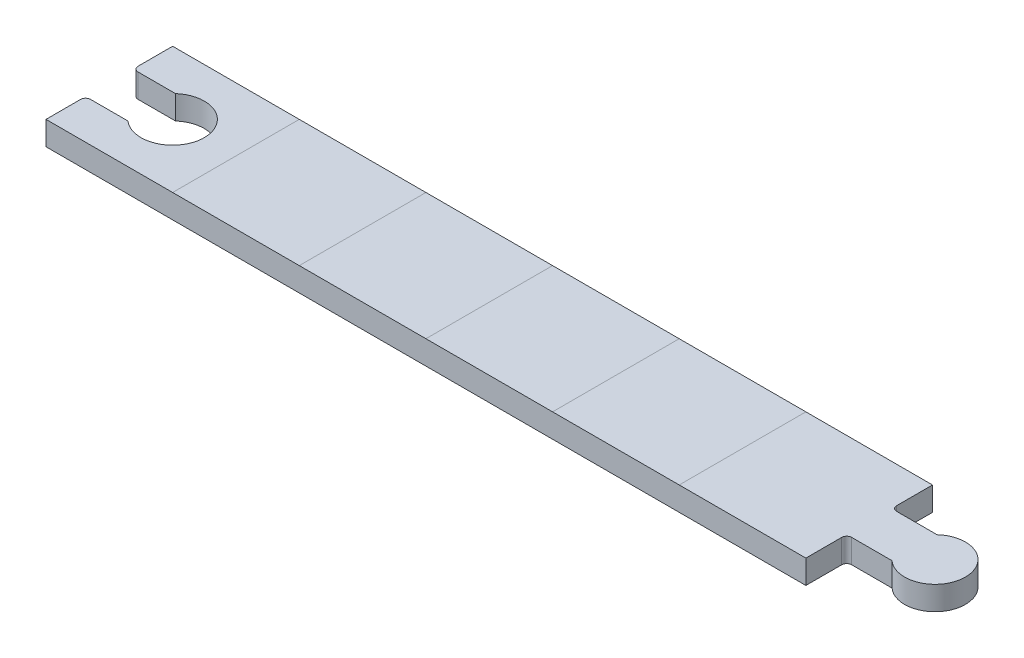
SolidWorks part; units mm, degrees
ref_plane "Front Plane" through (0, 0, 0) normal (0, 0, 1) x (1, 0, 0)
ref_plane "Top Plane" through (0, 0, 0) normal (0, 1, 0) x (1, 0, 0)
ref_plane "Right Plane" through (0, 0, 0) normal (1, 0, 0) x (0, 0, -1)
sketch "Sketch1" plane through (0, 0, 0) normal (0, 1, 0) x (1, 0, 0)
  line L0 (-76.2, 0) -> (95.5, 0) construction
  line L1 (-76.2, -12.7) -> (76.2, -12.7)
  line L2 (-76.2, -12.7) -> (-76.2, -4.7625)
  line L3 (-76.2, 12.7) -> (76.2, 12.7)
  line L4 (76.2, -12.7) -> (76.2, -4.5125)
  line L5 (-76.2, -12.7) -> (76.2, 12.7) construction
  line L6 (-76.2, 12.7) -> (76.2, -12.7) construction
  line L7 (76.2, 4.5125) -> (85.2954, 4.5125)
  line L8 (76.2, -4.5125) -> (85.2954, -4.5125)
  line L9 (76.2, 4.5125) -> (76.2, 12.7)
  line L10 (-67.7001, 4.7625) -> (-76.2, 4.7625)
  line L11 (-76.2, -4.7625) -> (-67.7001, -4.7625)
  line L12 (-76.2, 4.7625) -> (-76.2, 12.7)
  arc A0 (-67.7001, -4.7625) -> (-67.7001, 4.7625) centre (-63.5, 0) ccw
  arc A1 (85.2954, -4.5125) -> (85.2954, 4.5125) centre (89.4, 0) ccw
  point P0 (0, 0)
  dimension "D5" = 12.7
  dimension "D6" = 12.2
  dimension "D1" = 152.4
  dimension "D2" = 25.4
  dimension "D3" = 12.7
  dimension "D4" = 13.2
  dimension "D7" = 9.025
  dimension "D8" = 4.5125
  dimension "D9" = 9.525
  dimension "D10" = 4.7625
extrude "Boss-Extrude1" add sketch "Sketch1" along normal blind 4.7625
fillet "Fillet1" radius 1 4 edges at (-76.2, 2.3813, 4.7625) (-76.2, 2.3813, -4.7625) (76.2, 2.3813, -4.5125) (76.2, 2.3813, 4.5125)
sketch "Sketch2" plane through (0, 4.7625, 0) normal (0, 1, 0) x (1, 0, 0)
  line L0 (-50.8, 12.7) -> (-50.8, -12.7)
  line L1 (76.2, 12.7) -> (-76.2, 12.7) construction
  line L2 (-76.2, -12.7) -> (76.2, -12.7) construction
  line L3 (-76.2, 12.7) -> (-76.2, 5.7625) construction
  line L4 (-25.4, 12.7) -> (-25.4, -12.7)
  line L5 (0, 12.7) -> (0, -12.7)
  line L6 (25.4, 12.7) -> (25.4, -12.7)
  line L7 (50.8, 12.7) -> (50.8, -12.7)
  dimension "D1" = 25.4
  dimension "D2" = 5
split line "Split Line1"
